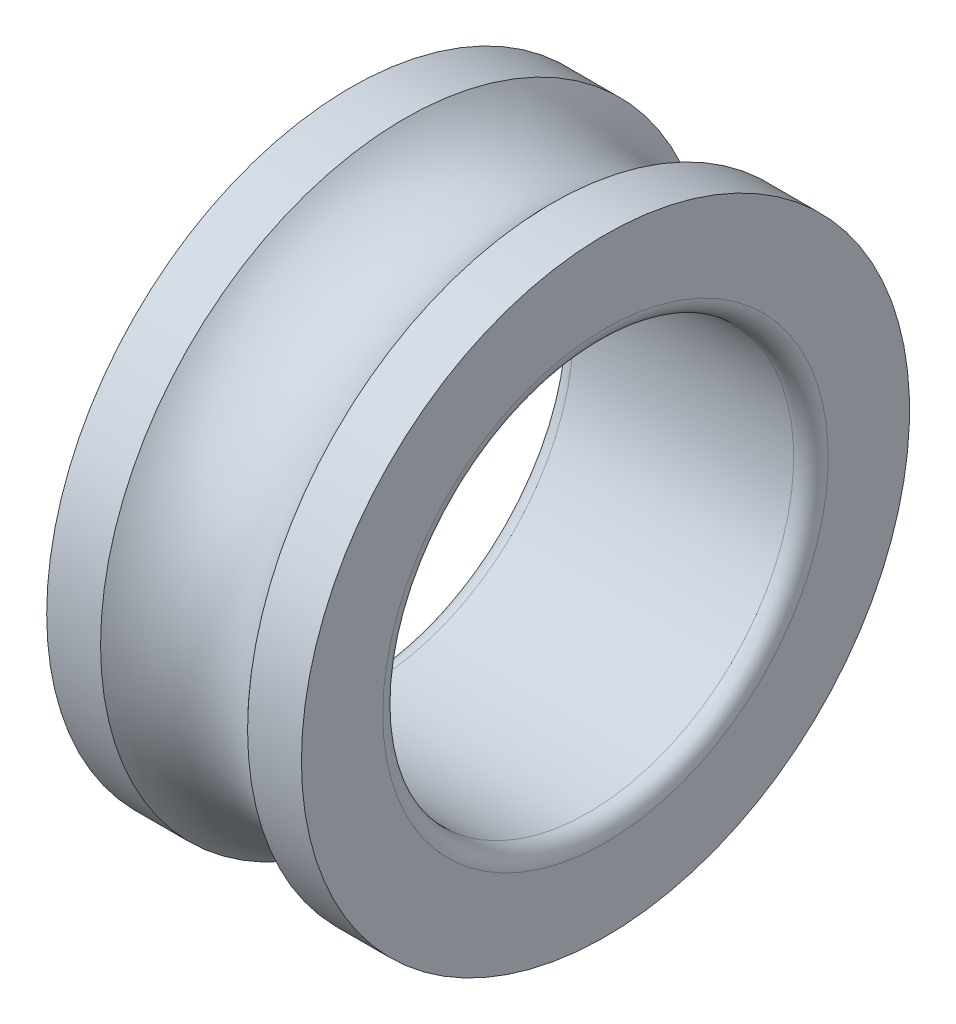
SolidWorks part; units mm, degrees
ref_plane "Front Plane" through (0, 0, 0) normal (0, 0, 1) x (1, 0, 0)
ref_plane "Top Plane" through (0, 0, 0) normal (0, 1, 0) x (1, 0, 0)
ref_plane "Right Plane" through (0, 0, 0) normal (1, 0, 0) x (0, 0, -1)
sketch "Sketch1" plane through (0, 0, 0) normal (0, 0, 1) x (1, 0, 0)
  line L0 (-42.9047, 0) -> (129.1042, 0) construction
  line L1 (4.9659, 37) -> (-1.5898, 37)
  line L2 (29.4102, 37) -> (22.8545, 37)
  line L3 (29.4102, 37) -> (29.4102, 27.1)
  line L4 (27.3102, 25) -> (0.5102, 25)
  line L5 (-1.5898, 37) -> (-1.5898, 27.1)
  line L6 (29.4102, 37) -> (-1.5898, 25) construction
  line L7 (29.4102, 25) -> (-1.5898, 37) construction
  arc A0 (4.9659, 37) -> (22.8545, 37) centre (13.9102, 45) ccw
  arc A1 (29.4102, 27.1) -> (27.3102, 25) centre (27.3102, 27.1) cw
  arc A2 (0.5102, 25) -> (-1.5898, 27.1) centre (0.5102, 27.1) cw
  point P3 (13.9102, 31)
  dimension "D5" = 12
  dimension "D6" = 2.1
  dimension "D1" = 25
  dimension "D2" = 31
  dimension "D3" = 37
  dimension "D4" = 8
revolve "Revolve1" add sketch "Sketch1" angle 360 about L0
